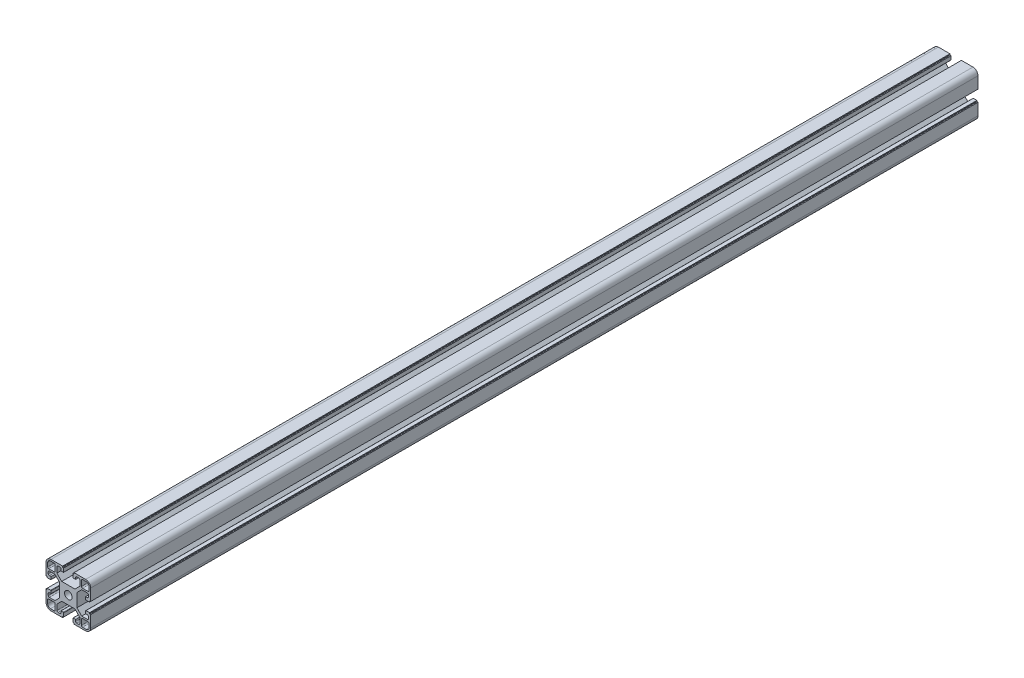
SolidWorks part; units mm, degrees
ref_plane "前视基准面" through (0, 0, 0) normal (0, 0, 1) x (1, 0, 0)
ref_plane "上视基准面" through (0, 0, 0) normal (0, 1, 0) x (1, 0, 0)
ref_plane "右视基准面" through (0, 0, 0) normal (1, 0, 0) x (0, 0, -1)
sketch "草图1" plane through (0, 0, 0) normal (0, 0, 1) x (1, 0, 0)
  line L0 (3.1381, -16.947) -> (7.8921, -16.947)
  line L1 (8.8921, -17.947) -> (8.8921, -21.201)
  line L2 (6.3921, -23.701) -> (3.1381, -23.701)
  line L3 (2.1381, -22.701) -> (2.1381, -17.947)
  line L4 (-21.3619, -17.947) -> (-21.3619, -22.701)
  line L5 (-22.3619, -23.701) -> (-25.6159, -23.701)
  line L6 (-28.1159, -21.201) -> (-28.1159, -17.947)
  line L7 (-27.1159, -16.947) -> (-22.3619, -16.947)
  line L8 (2.1381, 7.553) -> (2.1381, 12.307)
  line L9 (3.1381, 13.307) -> (6.3921, 13.307)
  line L10 (8.8921, 10.807) -> (8.8921, 7.553)
  line L11 (7.8921, 6.553) -> (3.1381, 6.553)
  line L12 (-22.3619, 6.553) -> (-27.1159, 6.553)
  line L13 (-28.1159, 7.553) -> (-28.1159, 10.807)
  line L14 (-25.6159, 13.307) -> (-22.3619, 13.307)
  line L15 (-21.3619, 12.307) -> (-21.3619, 7.553)
  line L16 (-1.9119, 0.7352) -> (2.4058, 5.053)
  line L17 (2.4058, 5.053) -> (7.3881, 5.053)
  line L18 (8.3881, 4.053) -> (8.3881, 2.403)
  line L19 (7.3881, 1.403) -> (5.8881, 1.403)
  line L20 (5.8881, 1.403) -> (5.8881, -0.797)
  line L21 (6.1881, -1.097) -> (9.3881, -1.097)
  line L22 (9.3881, -1.097) -> (9.3881, -0.297)
  line L23 (9.5881, -0.097) -> (10.3881, -0.097)
  line L24 (10.3881, -0.097) -> (10.3881, 10.303)
  line L25 (5.8881, 14.803) -> (-4.5119, 14.803)
  line L26 (-4.5119, 14.803) -> (-4.5119, 14.003)
  line L27 (-4.7119, 13.803) -> (-5.5119, 13.803)
  line L28 (-5.5119, 13.803) -> (-5.5119, 10.603)
  line L29 (-5.2119, 10.303) -> (-3.0119, 10.303)
  line L30 (-3.0119, 10.303) -> (-3.0119, 11.803)
  line L31 (-2.0119, 12.803) -> (-0.3619, 12.803)
  line L32 (0.6381, 11.803) -> (0.6381, 6.8207)
  line L33 (0.6381, 6.8207) -> (-3.6797, 2.503)
  line L34 (-3.6797, 2.503) -> (-15.5442, 2.503)
  line L35 (-15.5442, 2.503) -> (-19.8619, 6.8207)
  line L36 (-19.8619, 6.8207) -> (-19.8619, 11.803)
  line L37 (-18.8619, 12.803) -> (-17.2119, 12.803)
  line L38 (-16.2119, 11.803) -> (-16.2119, 10.303)
  line L39 (-16.2119, 10.303) -> (-14.0119, 10.303)
  line L40 (-13.7119, 10.603) -> (-13.7119, 13.803)
  line L41 (-13.7119, 13.803) -> (-14.5119, 13.803)
  line L42 (-14.7119, 14.003) -> (-14.7119, 14.803)
  line L43 (-14.7119, 14.803) -> (-25.1119, 14.803)
  line L44 (-29.6119, 10.303) -> (-29.6119, -0.097)
  line L45 (-29.6119, -0.097) -> (-28.8119, -0.097)
  line L46 (-28.6119, -0.297) -> (-28.6119, -1.097)
  line L47 (-28.6119, -1.097) -> (-25.4119, -1.097)
  line L48 (-25.1119, -0.797) -> (-25.1119, 1.403)
  line L49 (-25.1119, 1.403) -> (-26.6119, 1.403)
  line L50 (-27.6119, 2.403) -> (-27.6119, 4.053)
  line L51 (-26.6119, 5.053) -> (-21.6297, 5.053)
  line L52 (-21.6297, 5.053) -> (-17.3119, 0.7352)
  line L53 (-17.3119, 0.7352) -> (-17.3119, -11.1293)
  line L54 (-17.3119, -11.1293) -> (-21.6297, -15.447)
  line L55 (-21.6297, -15.447) -> (-26.6119, -15.447)
  line L56 (-27.6119, -14.447) -> (-27.6119, -12.797)
  line L57 (-26.6119, -11.797) -> (-25.1119, -11.797)
  line L58 (-25.1119, -11.797) -> (-25.1119, -9.597)
  line L59 (-25.4119, -9.297) -> (-28.6119, -9.297)
  line L60 (-28.6119, -9.297) -> (-28.6119, -10.097)
  line L61 (-28.8119, -10.297) -> (-29.6119, -10.297)
  line L62 (-29.6119, -10.297) -> (-29.6119, -20.697)
  line L63 (-25.1119, -25.197) -> (-14.7119, -25.197)
  line L64 (-14.7119, -25.197) -> (-14.7119, -24.397)
  line L65 (-14.5119, -24.197) -> (-13.7119, -24.197)
  line L66 (-13.7119, -24.197) -> (-13.7119, -20.997)
  line L67 (-14.0119, -20.697) -> (-16.2119, -20.697)
  line L68 (-16.2119, -20.697) -> (-16.2119, -22.197)
  line L69 (-17.2119, -23.197) -> (-18.8619, -23.197)
  line L70 (-19.8619, -22.197) -> (-19.8619, -17.2148)
  line L71 (-19.8619, -17.2148) -> (-15.5442, -12.897)
  line L72 (-15.5442, -12.897) -> (-3.6797, -12.897)
  line L73 (-3.6797, -12.897) -> (0.6381, -17.2148)
  line L74 (0.6381, -17.2148) -> (0.6381, -22.197)
  line L75 (-0.3619, -23.197) -> (-2.0119, -23.197)
  line L76 (-3.0119, -22.197) -> (-3.0119, -20.697)
  line L77 (-3.0119, -20.697) -> (-5.2119, -20.697)
  line L78 (-5.5119, -20.997) -> (-5.5119, -24.197)
  line L79 (-5.5119, -24.197) -> (-4.7119, -24.197)
  line L80 (-4.5119, -24.397) -> (-4.5119, -25.197)
  line L81 (-4.5119, -25.197) -> (5.8881, -25.197)
  line L82 (10.3881, -20.697) -> (10.3881, -10.297)
  line L83 (10.3881, -10.297) -> (9.5881, -10.297)
  line L84 (9.3881, -10.097) -> (9.3881, -9.297)
  line L85 (9.3881, -9.297) -> (6.1881, -9.297)
  line L86 (5.8881, -9.597) -> (5.8881, -11.797)
  line L87 (5.8881, -11.797) -> (7.3881, -11.797)
  line L88 (8.3881, -12.797) -> (8.3881, -14.447)
  line L89 (7.3881, -15.447) -> (2.4058, -15.447)
  line L90 (2.4058, -15.447) -> (-1.9119, -11.1293)
  line L91 (-1.9119, -11.1293) -> (-1.9119, 0.7352)
  arc A0 (8.8921, -17.947) -> (7.8921, -16.947) centre (7.8921, -17.947) ccw
  arc A1 (6.3921, -23.701) -> (8.8921, -21.201) centre (6.3921, -21.201) ccw
  arc A2 (2.1381, -22.701) -> (3.1381, -23.701) centre (3.1381, -22.701) ccw
  arc A3 (3.1381, -16.947) -> (2.1381, -17.947) centre (3.1381, -17.947) ccw
  arc A4 (-22.3619, -23.701) -> (-21.3619, -22.701) centre (-22.3619, -22.701) ccw
  arc A5 (-28.1159, -21.201) -> (-25.6159, -23.701) centre (-25.6159, -21.201) ccw
  arc A6 (-27.1159, -16.947) -> (-28.1159, -17.947) centre (-27.1159, -17.947) ccw
  arc A7 (-21.3619, -17.947) -> (-22.3619, -16.947) centre (-22.3619, -17.947) ccw
  arc A8 (3.1381, 13.307) -> (2.1381, 12.307) centre (3.1381, 12.307) ccw
  arc A9 (8.8921, 10.807) -> (6.3921, 13.307) centre (6.3921, 10.807) ccw
  arc A10 (7.8921, 6.553) -> (8.8921, 7.553) centre (7.8921, 7.553) ccw
  arc A11 (2.1381, 7.553) -> (3.1381, 6.553) centre (3.1381, 7.553) ccw
  arc A12 (-28.1159, 7.553) -> (-27.1159, 6.553) centre (-27.1159, 7.553) ccw
  arc A13 (-25.6159, 13.307) -> (-28.1159, 10.807) centre (-25.6159, 10.807) ccw
  arc A14 (-21.3619, 12.307) -> (-22.3619, 13.307) centre (-22.3619, 12.307) ccw
  arc A15 (-22.3619, 6.553) -> (-21.3619, 7.553) centre (-22.3619, 7.553) ccw
  circle A16 centre (-9.6119, -5.197) radius 3.4
  arc A17 (8.3881, 4.053) -> (7.3881, 5.053) centre (7.3881, 4.053) ccw
  arc A18 (7.3881, 1.403) -> (8.3881, 2.403) centre (7.3881, 2.403) ccw
  arc A19 (5.8881, -0.797) -> (6.1881, -1.097) centre (6.1881, -0.797) ccw
  arc A20 (9.5881, -0.097) -> (9.3881, -0.297) centre (9.5881, -0.297) ccw
  arc A21 (10.3881, 10.303) -> (5.8881, 14.803) centre (5.8881, 10.303) ccw
  arc A22 (-4.7119, 13.803) -> (-4.5119, 14.003) centre (-4.7119, 14.003) ccw
  arc A23 (-5.5119, 10.603) -> (-5.2119, 10.303) centre (-5.2119, 10.603) ccw
  arc A24 (-2.0119, 12.803) -> (-3.0119, 11.803) centre (-2.0119, 11.803) ccw
  arc A25 (0.6381, 11.803) -> (-0.3619, 12.803) centre (-0.3619, 11.803) ccw
  arc A26 (-18.8619, 12.803) -> (-19.8619, 11.803) centre (-18.8619, 11.803) ccw
  arc A27 (-16.2119, 11.803) -> (-17.2119, 12.803) centre (-17.2119, 11.803) ccw
  arc A28 (-14.0119, 10.303) -> (-13.7119, 10.603) centre (-14.0119, 10.603) ccw
  arc A29 (-14.7119, 14.003) -> (-14.5119, 13.803) centre (-14.5119, 14.003) ccw
  arc A30 (-25.1119, 14.803) -> (-29.6119, 10.303) centre (-25.1119, 10.303) ccw
  arc A31 (-28.6119, -0.297) -> (-28.8119, -0.097) centre (-28.8119, -0.297) ccw
  arc A32 (-25.4119, -1.097) -> (-25.1119, -0.797) centre (-25.4119, -0.797) ccw
  arc A33 (-27.6119, 2.403) -> (-26.6119, 1.403) centre (-26.6119, 2.403) ccw
  arc A34 (-26.6119, 5.053) -> (-27.6119, 4.053) centre (-26.6119, 4.053) ccw
  arc A35 (-27.6119, -14.447) -> (-26.6119, -15.447) centre (-26.6119, -14.447) ccw
  arc A36 (-26.6119, -11.797) -> (-27.6119, -12.797) centre (-26.6119, -12.797) ccw
  arc A37 (-25.1119, -9.597) -> (-25.4119, -9.297) centre (-25.4119, -9.597) ccw
  arc A38 (-28.8119, -10.297) -> (-28.6119, -10.097) centre (-28.8119, -10.097) ccw
  arc A39 (-29.6119, -20.697) -> (-25.1119, -25.197) centre (-25.1119, -20.697) ccw
  arc A40 (-14.5119, -24.197) -> (-14.7119, -24.397) centre (-14.5119, -24.397) ccw
  arc A41 (-13.7119, -20.997) -> (-14.0119, -20.697) centre (-14.0119, -20.997) ccw
  arc A42 (-17.2119, -23.197) -> (-16.2119, -22.197) centre (-17.2119, -22.197) ccw
  arc A43 (-19.8619, -22.197) -> (-18.8619, -23.197) centre (-18.8619, -22.197) ccw
  arc A44 (-0.3619, -23.197) -> (0.6381, -22.197) centre (-0.3619, -22.197) ccw
  arc A45 (-3.0119, -22.197) -> (-2.0119, -23.197) centre (-2.0119, -22.197) ccw
  arc A46 (-5.2119, -20.697) -> (-5.5119, -20.997) centre (-5.2119, -20.997) ccw
  arc A47 (-4.5119, -24.397) -> (-4.7119, -24.197) centre (-4.7119, -24.397) ccw
  arc A48 (5.8881, -25.197) -> (10.3881, -20.697) centre (5.8881, -20.697) ccw
  arc A49 (9.3881, -10.097) -> (9.5881, -10.297) centre (9.5881, -10.097) ccw
  arc A50 (6.1881, -9.297) -> (5.8881, -9.597) centre (6.1881, -9.597) ccw
  arc A51 (8.3881, -12.797) -> (7.3881, -11.797) centre (7.3881, -12.797) ccw
  arc A52 (7.3881, -15.447) -> (8.3881, -14.447) centre (7.3881, -14.447) ccw
extrude "凸台-拉伸1" add sketch "草图1" along normal blind 795
